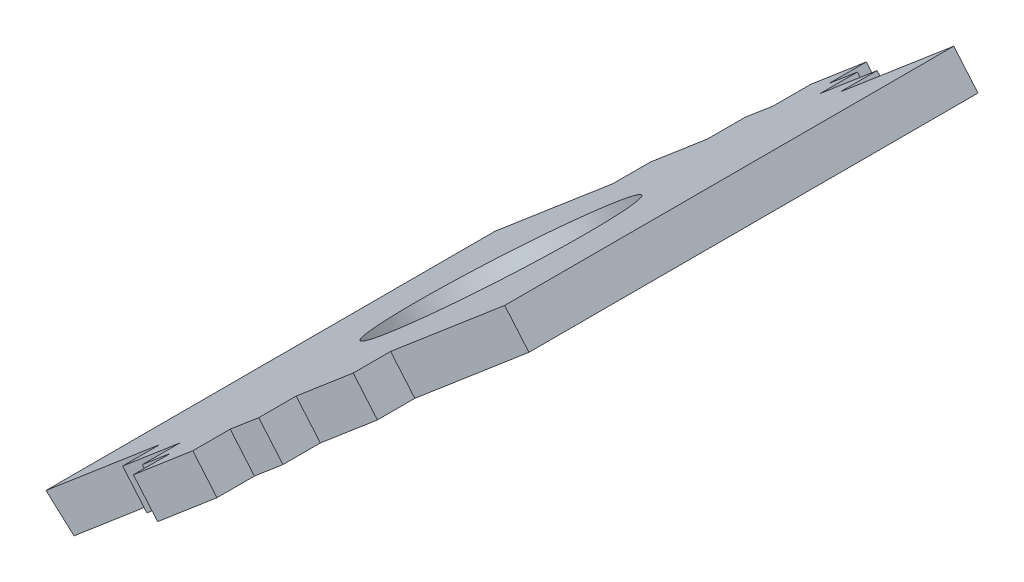
SolidWorks part; units mm, degrees
ref_plane "Front Plane" through (0, 0, 0) normal (0, 0, 1) x (1, 0, 0)
ref_plane "Top Plane" through (0, 0, 0) normal (0, 1, 0) x (1, 0, 0)
ref_plane "Right Plane" through (0, 0, 0) normal (1, 0, 0) x (0, 0, -1)
sketch "Sketch1" plane through (0, 0, 0) normal (0, 0, 1) x (1, 0, 0)
  line L0 (-104.4257, 293.5583) -> (-143.0227, 260.7741)
  line L1 (-143.0227, 260.7741) -> (-145.398, 262.9223)
  line L2 (-145.398, 262.9223) -> (-106.4812, 295.9782)
  line L3 (-106.4812, 295.9782) -> (-104.4257, 293.5583)
  spline S0 degree 3 poles (-143.0227, 260.7741) (-149.7227, 266.9607) (-161.8696, 276.8202) (-182.4545, 272.3991) (-187.4302, 266.3755) (-189.0974, 258.9326) (-190.9202, 258.914) knots 0 0 0 0 0.461149 0.724472 0.870774 1 1 1 1 construction
  dimension "D1" = 3.175
extrude "Boss-Extrude1" add sketch "Sketch1" along normal blind 47.625 and the other way blind 9.525 contours L0 L1 L2 L3
sketch "Sketch2" plane through (-188.6105, 222.052, 0) normal (0.6474, -0.7622, 0) x (0.7622, 0.6474, 0)
  line L0 (68.3335, -6.35) -> (122.4143, -6.35) construction
  line L1 (110.4546, -9.525) -> (88.2296, -9.525)
  line L3 (91.4046, -6.35) -> (88.2296, -6.35)
  line L4 (88.2296, -9.525) -> (88.2296, -6.35)
  line L5 (122.4143, -3.175) -> (68.3335, -3.175) construction
  line L6 (59.8134, -9.525) -> (82.0384, -9.525)
  line L7 (110.4546, 38.1) -> (118.1924, 38.1)
  line L8 (78.8634, -6.35) -> (82.0384, -6.35)
  line L9 (82.0384, -9.525) -> (82.0384, -6.35)
  line L10 (110.4546, -9.525) -> (110.4546, 47.625) construction
  line L12 (97.7546, -3.175) -> (91.4046, -3.175)
  line L13 (91.4046, -6.35) -> (91.4046, -3.175)
  line L14 (110.4546, 0) -> (59.8134, 0) construction
  line L15 (110.4546, -9.525) -> (59.8134, -9.525) construction
  line L16 (110.4546, 47.625) -> (118.1924, 47.625)
  line L17 (72.5134, -3.175) -> (78.8634, -3.175)
  line L18 (78.8634, -6.35) -> (78.8634, -3.175)
  line L19 (118.1924, 38.1) -> (118.1924, 47.625)
  line L20 (59.3938, 38.1) -> (50.3391, 38.1)
  line L21 (59.8134, 0) -> (72.5134, 0)
  line L22 (72.5134, -3.175) -> (72.5134, 0)
  line L23 (122.4143, 44.45) -> (68.3335, 44.45) construction
  line L24 (59.8134, 0) -> (54.8308, 0)
  line L26 (110.4546, 0) -> (97.7546, 0)
  line L27 (97.7546, -3.175) -> (97.7546, 0)
  line L28 (110.4546, 47.625) -> (88.2296, 47.625)
  line L30 (91.4046, 44.45) -> (88.2296, 44.45)
  line L31 (88.2296, 47.625) -> (88.2296, 44.45)
  line L32 (68.3335, 41.275) -> (122.4143, 41.275) construction
  line L33 (59.3938, 47.625) -> (50.3391, 47.625)
  line L35 (97.7546, 41.275) -> (91.4046, 41.275)
  line L36 (91.4046, 44.45) -> (91.4046, 41.275)
  line L37 (110.4546, 38.1) -> (59.8134, 38.1) construction
  line L38 (59.8134, -9.525) -> (54.8308, -9.525)
  line L40 (110.4546, 38.1) -> (97.7546, 38.1)
  line L41 (97.7546, 41.275) -> (97.7546, 38.1)
  line L42 (54.8308, 0) -> (54.8308, -9.525)
  line L43 (59.3938, 47.625) -> (81.6188, 47.625)
  line L45 (78.4438, 44.45) -> (81.6188, 44.45)
  line L46 (81.6188, 47.625) -> (81.6188, 44.45)
  line L47 (110.4546, 0) -> (113.6799, 0)
  line L49 (72.0938, 41.275) -> (78.4438, 41.275)
  line L50 (78.4438, 44.45) -> (78.4438, 41.275)
  line L51 (50.3391, 38.1) -> (50.3391, 47.625)
  line L53 (59.3938, 38.1) -> (72.0938, 38.1)
  line L54 (72.0938, 41.275) -> (72.0938, 38.1)
  line L55 (110.4546, -9.525) -> (113.6799, -9.525)
  line L56 (113.6799, 0) -> (113.6799, -9.525)
  circle A0 centre (85.0546, 19.05) radius 9.525
  dimension "D13" = 19.05
  dimension "D14" = 25.4
  dimension "D15" = 28.575
  dimension "D1" = 12.7
  dimension "D2" = 12.7
  dimension "D3" = 6.35
  dimension "D4" = 6.35
  dimension "D5" = 3.175
  dimension "D6" = 3.175
  dimension "D7" = 12.7
  dimension "D8" = 12.7
  dimension "D9" = 6.35
  dimension "D10" = 6.35
  dimension "D11" = 3.175
  dimension "D12" = 3.175
extrude "Cut-Extrude1" cut sketch "Sketch2" against normal through all
